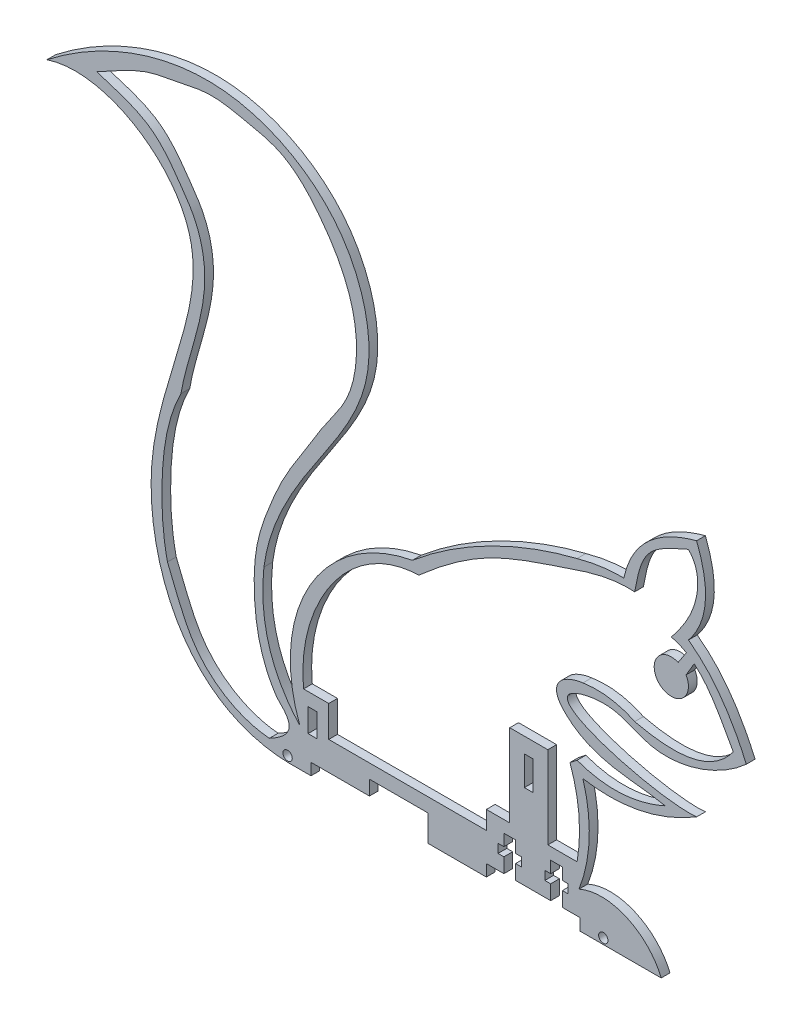
SolidWorks part; units mm, degrees
ref_plane "前视" through (0, 0, 0) normal (0, 0, 1) x (1, 0, 0)
ref_plane "上视" through (0, 0, 0) normal (0, 1, 0) x (1, 0, 0)
ref_plane "右视" through (0, 0, 0) normal (1, 0, 0) x (0, 0, -1)
sketch "草图1" plane through (0, 0, 0) normal (0, 0, 1) x (1, 0, 0)
  line L0 (146, 0) -> (140, 0)
  line L1 (46.0876, -4) -> (54, -4)
  line L2 (94, -4) -> (114, -4)
  line L3 (51.4515, 20.4701) -> (60.0762, 20.4701)
  line L4 (182.4157, 96.6711) -> (179.6125, 92.3898)
  line L5 (162, -4) -> (146, -4)
  line L6 (146, -4) -> (146, 0)
  line L7 (146, -4) -> (173.8066, -4)
  line L8 (54, -4) -> (54, 0)
  line L9 (46.0876, -4) -> (54, -4)
  line L10 (54, 0) -> (74, 0)
  line L11 (114, -4) -> (94, -4)
  line L12 (84, 27.8711) -> (84, -21.6643) construction
  line L13 (-522.4497, 2.8715) -> (-324.1735, 2.8715)
  line L14 (130, 32) -> (130, 39)
  line L15 (-480.9604, -289.6777) -> (-282.6843, -289.6777)
  line L16 (138, -15.9655) -> (138, 24.4172) construction
  line L17 (94, 5) -> (74, 5)
  line L18 (136, 12) -> (140, 12)
  line L19 (140, 12) -> (140, 8)
  line L20 (140, 8) -> (142, 8)
  line L21 (142, 8) -> (142, 5)
  line L22 (142, 5) -> (140, 5)
  line L23 (140, 5) -> (140, 0)
  line L24 (114, 16.0406) -> (114, -46.0459) construction
  line L25 (54, 34.8086) -> (54, -60.6695) construction
  line L26 (60.0762, 20.4701) -> (60.0762, 9.8161)
  line L27 (60.0762, 9.8161) -> (114, 9.8161)
  line L28 (114, 9.8161) -> (114, 16.0406)
  line L29 (114, 16.0406) -> (122, 16.0406)
  line L30 (136, 5) -> (136, 0)
  line L31 (134, 5) -> (136, 5)
  line L32 (134, 8) -> (134, 5)
  line L33 (136, 8) -> (134, 8)
  line L34 (136, 12) -> (136, 8)
  line L35 (122, 16.0406) -> (122, 44.2502)
  line L36 (122, 44.2502) -> (135.0349, 44.2502)
  line L37 (135.0349, 44.2502) -> (135.0349, 16.0406)
  line L38 (135.0349, 16.0406) -> (145.0325, 16.0406)
  line L40 (185.1032, 94.7597) -> (182.2996, 90.0294)
  line L41 (136, 0) -> (124, 0)
  line L44 (130, 39) -> (127, 39)
  line L45 (122, -15.9655) -> (122, 24.4172) construction
  line L46 (127, 39) -> (127, 29)
  line L47 (56, 16) -> (56, 8)
  line L48 (56, 16) -> (53, 16)
  line L49 (53, 16) -> (53, 8)
  line L50 (124, 12) -> (124, 8)
  line L51 (124, 8) -> (126, 8)
  line L52 (56, 8) -> (53, 8)
  line L57 (94, -4) -> (94, 5)
  line L62 (126, 8) -> (126, 5)
  line L63 (126, 5) -> (124, 5)
  line L64 (124, 5) -> (124, 0)
  line L65 (120, 5) -> (120, 0)
  line L66 (118, 5) -> (120, 5)
  line L67 (74, 5) -> (74, 0)
  line L69 (130, 29) -> (130, 32)
  line L70 (127, 29) -> (130, 29)
  line L71 (118, 8) -> (118, 5)
  line L72 (120, 8) -> (118, 8)
  line L73 (120, 12) -> (120, 8)
  line L74 (124, 12) -> (120, 12)
  line L75 (114, 0) -> (120, 0)
  line L76 (114, 0) -> (114, -4)
  circle A0 centre (154, -2) radius 1.6
  circle A1 centre (46, -2) radius 1.6
  arc A2 (145.6856, 8.2715) -> (147.0327, 41.6863) centre (98.0705, 26.9256) ccw
  arc A3 (88.6997, 77.1984) -> (50.1606, 9.0423) centre (98.0705, 26.9256) ccw
  arc A4 (179.6125, 92.3898) -> (182.2996, 90.0294) centre (177.2723, 87.0159) ccw
  arc A5 (-439.4513, 13.0978) -> (-438.3288, 40.9434) centre (-479.1306, 28.6428) ccw
  arc A6 (-520.2051, 17.2861) -> (-519.0555, 13.7401) centre (-479.1306, 28.6428) ccw
  circle A7 centre (-432.9689, 98.7552) radius 4.6348
  arc A8 (-397.9621, -279.4514) -> (-396.8395, -251.6057) centre (-437.6413, -263.9064) ccw
  arc A9 (-478.7159, -275.2631) -> (-477.5663, -278.8091) centre (-437.6413, -263.9064) ccw
  circle A10 centre (-391.4797, -193.794) radius 4.6348
  spline S0 degree 3 poles (-36.3284, 162.9819) (-19.2126, 176.3931) (18.6726, 193.5124) (67.348, 167.6864) (79.5493, 122.0971) (55.564, 90.9269) (41.4676, 66.4689) (38.376, 53.451) (37.8938, 49.7921) knots 0 0 0 0 0.268932 0.436077 0.592251 0.76171 0.880208 0.924853 0.924853 0.924853 0.924853
  spline S1 degree 3 poles (-36.3284, 162.9819) (-16.9851, 169.4292) (20.273, 146.3451) (9.1359, 98.5161) (-9.2973, 48.3959) (11.0873, -2.8334) (46.0876, -4) knots 0 0 0 0 0.267966 0.41605 0.610525 1 1 1 1
  spline S2 degree 3 poles (37.8938, 49.7921) (36.1883, 33.2874) (40.2772, 19.7042) (50.1606, 9.0423) knots 0 0 0 0 0.573192 0.573192 0.573192 0.573192
  spline S3 degree 3 poles (-19.2556, 167.961) (-12.9857, 165.9143) (-0.5109, 162.8308) (8.1114, 150.5788) (15.1144, 140.6331) (21.0292, 119.2496) (11.7883, 100.4998) (9.5379, 87.0159) knots 0 0 0 0 0.204135 0.357425 0.435141 0.570451 1 1 1 1
  spline S4 degree 2 poles (145.0325, 105.8702) (153.5131, 108.2354) (161.0327, 108.0832) knots 0 0 0 0.216189 0.216189 0.216189
  spline S5 degree 3 poles (145.6856, 8.2715) (156.7589, 13.1534) (169.5876, 6.4339) (173.8066, -4) knots 0 0 0 0 1 1 1 1
  spline S6 degree 3 poles (202.9252, 73.8875) (194.678, 66.3063) (175.1614, 58.1049) (157.452, 69.3966) (123.7384, 61.5285) (173.3068, 48.4798) (185.9217, 49.7921) knots 0 0 0 0 0.328041 0.450974 0.579788 1 1 1 1
  spline S7 degree 3 poles (88.6997, 77.1984) (105.0696, 91.0142) (125.0882, 100.9361) (145.0325, 105.8702) knots 0.574998 0.574998 0.574998 0.574998 1 1 1 1
  spline S8 degree 3 poles (147.0327, 41.6863) (160.3135, 39.4423) (173.2765, 42.1442) (185.9217, 49.7921) knots 0.296717 0.296717 0.296717 0.296717 1 1 1 1
  spline S9 degree 3 poles (161.0327, 108.0832) (163.5054, 119.9891) (171.8018, 127.828) (185.9217, 131.5998) knots 0.19371 0.19371 0.19371 0.19371 1 1 1 1
  spline S10 degree 3 poles (185.9217, 131.5998) (190.7847, 119.2377) (189.8553, 108.9702) (183.1336, 100.7973) knots 0 0 0 0 0.750226 0.750226 0.750226 0.750226
  spline S11 degree 2 poles (183.1336, 100.7973) (194.9205, 92.2959) (202.9252, 73.8875) knots 0.571131 0.571131 0.571131 1 1 1
  spline S12 degree 3 poles (9.5379, 87.0159) (4.7217, 77.5726) (2.217, 59.7515) (3.3058, 41.9819) (4.9099, 34.8085) knots 0 0 0 0 0.29535 0.502013 0.502013 0.502013 0.502013
  spline S13 degree 3 poles (-591.1296, 142.0231) (-576.8665, 153.1991) (-545.2955, 167.4652) (-504.7327, 145.9435) (-494.5649, 107.9524) (-514.5527, 81.9772) (-526.2997, 61.5956) (-528.876, 50.7474) (-529.2779, 47.6982) knots 0 0 0 0 0.268932 0.436077 0.592251 0.76171 0.880208 0.924853 0.924853 0.924853 0.924853
  spline S14 degree 3 poles (-591.1296, 142.0231) (-575.0102, 147.3958) (-543.9619, 128.1591) (-553.2428, 88.3016) (-568.6038, 46.5348) (-551.6166, 3.8436) (-522.4497, 2.8715) knots 0 0 0 0 0.267966 0.41605 0.610525 1 1 1 1
  spline S15 degree 3 poles (-529.2779, 47.6982) (-530.6991, 33.9443) (-527.2917, 22.625) (-519.0555, 13.7401) knots 0 0 0 0 0.573192 0.573192 0.573192 0.573192
  spline S16 degree 3 poles (-517.915, 10.9832) (-517.9028, 11.4916) (-517.8853, 11.9984) (-517.8624, 12.5036) knots 0.020929 0.020929 0.020929 0.020929 0.032656 0.032656 0.032656 0.032656
  spline S17 degree 3 poles (-464.3143, 98.7552) (-468.3801, 84.0817) (-495.7138, 79.019) (-523.366, 52.6511) (-525.6034, 29.9505) (-520.2051, 17.2861) knots 0 0 0 0 0.372207 0.647473 0.960768 0.960768 0.960768 0.960768
  spline S18 degree 3 poles (-439.4513, 13.0978) (-430.2235, 17.166) (-419.533, 11.5664) (-416.0172, 2.8715) knots 0 0 0 0 1 1 1 1
  spline S19 degree 2 poles (-410.1859, 58.3749) (-407.1614, 66.1873) (-398.0091, 66.3483) knots 0 0 0 1 1 1
  spline S20 degree 3 poles (-398.0091, 66.3483) (-409.4604, 79.106) (-424.3131, 55.6941) (-436.7276, 58.21) knots 0 0 0 0 1 1 1 1
  spline S21 degree 3 poles (-438.3288, 40.9434) (-427.2614, 39.0734) (-417.9637, 56.5323) (-410.1859, 58.3749) knots 0.296717 0.296717 0.296717 0.296717 1 1 1 1
  spline S22 degree 2 poles (-467.9513, 122.3306) (-451.5205, 125.6186) (-445.4262, 105.6299) knots 0 0 0 1 1 1
  spline S23 degree 2 poles (-445.4262, 105.6299) (-422.6946, 115.273) (-407.7631, 93.1472) knots 0 0 0 1 1 1
  spline S24 degree 3 poles (-407.7631, 93.1472) (-406.9144, 71.3282) (-446.605, 81.314) (-436.7276, 58.21) knots 0 0 0 0 1 1 1 1
  spline S25 degree 2 poles (-464.3143, 98.7552) (-461.6342, 111.2703) (-467.9513, 122.3306) knots 0 0 0 1 1 1
  spline S26 degree 3 poles (-549.6404, -150.5261) (-535.3773, -139.3501) (-503.8062, -125.084) (-463.2434, -146.6057) (-453.0757, -184.5968) (-473.0634, -210.572) (-484.8105, -230.9536) (-487.3868, -241.8018) (-487.7886, -244.851) knots 0 0 0 0 0.268932 0.436077 0.592251 0.76171 0.880208 0.924853 0.924853 0.924853 0.924853
  spline S27 degree 3 poles (-549.6404, -150.5261) (-533.521, -145.1534) (-502.4726, -164.3901) (-511.7535, -204.2476) (-527.1145, -246.0144) (-510.1274, -288.7055) (-480.9604, -289.6777) knots 0 0 0 0 0.267966 0.41605 0.610525 1 1 1 1
  spline S28 degree 3 poles (-487.7886, -244.851) (-489.2099, -258.6048) (-485.8024, -269.9242) (-477.5663, -278.8091) knots 0 0 0 0 0.573192 0.573192 0.573192 0.573192
  spline S29 degree 3 poles (-476.4257, -281.566) (-476.4136, -281.0576) (-476.396, -280.5508) (-476.3732, -280.0456) knots 0.020929 0.020929 0.020929 0.020929 0.032656 0.032656 0.032656 0.032656
  spline S30 degree 3 poles (-463.9556, -305.2924) (-487.8284, -289.2263) (-486.1729, -240.9842) (-456.6237, -187.9796) (-411.5629, -182.8663) (-403.1964, -157.3081) (-404.2191, -146.3103) knots 0 0 0 0 0.380882 0.666688 0.828463 1 1 1 1
  spline S31 degree 3 poles (-397.9621, -279.4514) (-388.7343, -275.3832) (-378.0437, -280.9828) (-374.5279, -289.6777) knots 0 0 0 0 1 1 1 1
  spline S32 degree 2 poles (-368.6967, -234.1743) (-365.6721, -226.3619) (-356.5198, -226.2009) knots 0 0 0 1 1 1
  spline S33 degree 3 poles (-356.5198, -226.2009) (-367.9711, -213.4432) (-382.8239, -236.8551) (-395.2383, -234.3392) knots 0 0 0 0 1 1 1 1
  spline S34 degree 3 poles (-396.8395, -251.6057) (-385.7722, -253.4758) (-376.4745, -236.0169) (-368.6967, -234.1743) knots 0.296717 0.296717 0.296717 0.296717 1 1 1 1
  spline S35 degree 2 poles (-404.2191, -146.3103) (-387.9349, -153.5513) (-391.4797, -173.2203) knots 0 0 0 1 1 1
  spline S36 degree 3 poles (-391.4797, -173.2203) (-379.3158, -179.8671) (-363.2696, -192.5607) (-368.6967, -208.8389) knots 0 0 0 0 1 1 1 1
  spline S37 degree 3 poles (-368.6967, -208.8389) (-376.5591, -217.4133) (-396.8936, -205.4289) (-422.9752, -229.7003) (-395.2383, -234.3392) knots 0 0 0 0 0.432826 1 1 1 1
  spline S38 degree 2 poles (142.6034, 44.2502) (147.5268, 30.4593) (145.0325, 16.0406) knots 0 0 0 1 1 1
  spline S39 degree 3 poles (51.4515, 20.4701) (50.4896, 30.5137) (55.558, 55.245) (75.5729, 73.3964) (90.8813, 73.8875) knots 0 0 0 0 0.412378 1 1 1 1
  spline S40 degree 2 poles (147.0327, 70.0421) (156.3076, 71.4694) (164.7313, 67.41) knots 0 0 0 1 1 1
  spline S41 degree 1 poles (142.6034, 44.2502) (145.0325, 46.1176) knots 0 0 1 1
  spline S42 degree 2 poles (145.0325, 46.1176) (159.7653, 40.733) (175.1762, 47.6982) knots 0 0 0 1 1 1
  spline S43 degree 3 poles (175.1762, 47.6982) (164.1412, 50.025) (147.7608, 48.3297) (135.7608, 63.723) (140, 67.41) knots 0 0 0 0 0.728358 1 1 1 1
  spline S44 degree 3 poles (90.8813, 73.8875) (98.412, 80.5274) (113.6534, 92.2014) (139.7928, 100.5701) (156.0235, 106.3892) (164.7313, 105.8702) knots 0 0 0 0 0.369785 0.690055 1 1 1 1
  spline S45 degree 3 poles (164.7313, 105.8702) (165.5792, 110.3212) (167.3808, 121.7216) (178.5347, 125.4754) (183.1336, 127.6604) knots 0 0 0 0 0.468748 1 1 1 1
  spline S46 degree 3 poles (183.1336, 127.6604) (186.3889, 124.298) (187.2483, 112.8811) (181.1694, 103.539) (177.2723, 98.7552) knots 0 0 0 0 0.411387 1 1 1 1
  spline S47 degree 2 poles (177.2723, 98.7552) (180.066, 98.0602) (182.4157, 96.6711) knots 0 0 0 0.170128 0.170128 0.170128
  spline S48 degree 3 poles (140, 67.41) (141.9434, 68.8854) (144.6461, 69.7278) (147.0327, 70.0421) knots 0 0 0 0 0.121418 0.121418 0.121418 0.121418
  spline S49 degree 3 poles (185.1032, 94.7597) (191.0985, 89.7628) (194.8207, 81.5542) (198.475, 75.3225) knots 0.272967 0.272967 0.272967 0.272967 1 1 1 1
  spline S50 degree 3 poles (-19.2556, 167.961) (-13.1979, 171.1164) (-4.5099, 176.7517) (8.9087, 178.6809) (19.7231, 181.4514) (31.5448, 178.8068) (46.0452, 175.8752) (56.0412, 165.1333) (63.8593, 153.499) (68.6771, 142.0325) (70.3364, 128.0272) (67.4386, 113.8182) (59.0276, 103.2257) (52.4014, 91.9133) (45.3006, 81.4514) (39.6373, 68.6518) (34.9568, 56.0101) (34.0043, 36.3441) (36.6173, 21.7309) (42.2805, 13.4657) knots 0 0 0 0 0.08455 0.121132 0.164743 0.218457 0.266344 0.342105 0.387006 0.438418 0.491502 0.557394 0.608146 0.654397 0.717408 0.761563 0.824889 0.879957 1 1 1 1
  spline S51 degree 3 poles (42.2805, 13.4657) (46.6, 9.2344) (50.1556, 5.4645) (39.7729, 0) knots 0.928992 0.928992 0.928992 0.928992 1 1 1 1
  spline S52 degree 3 poles (164.7313, 67.41) (177.1393, 64.5644) (190.2646, 64.1525) (198.475, 75.3225) knots 0.410742 0.410742 0.410742 0.410742 1 1 1 1
  spline S53 degree 3 poles (4.9099, 34.8085) (7.9623, 27.7328) (13.379, 10.1618) (30.1818, 0.7713) (39.7729, 0) knots 0 0 0 0 0.453956 1 1 1 1
  point P41 (138, 12)
  point P86 (122, 12)
  dimension "D11" = 2
  dimension "D12" = 2
  dimension "D13" = 2
  dimension "D25" = 3.2
  dimension "D26" = 3.2
  dimension "D7" = 4
  dimension "D4" = 16
  dimension "D8" = 38
  dimension "D9" = 3
  dimension "D10" = 10
  dimension "D14" = 3
  dimension "D15" = 5
  dimension "D16" = 12
  dimension "D17" = 8
  dimension "D18" = 10
  dimension "D19" = 10
  dimension "D20" = 9
  dimension "D21" = 30
  dimension "D22" = 30
  dimension "D32" = 2
  dimension "D35" = 29
  dimension "D37" = 3
  dimension "D51" = 3
  dimension "D53" = 8
extrude "凸台-拉伸1" add sketch "草图1" along normal blind 3
